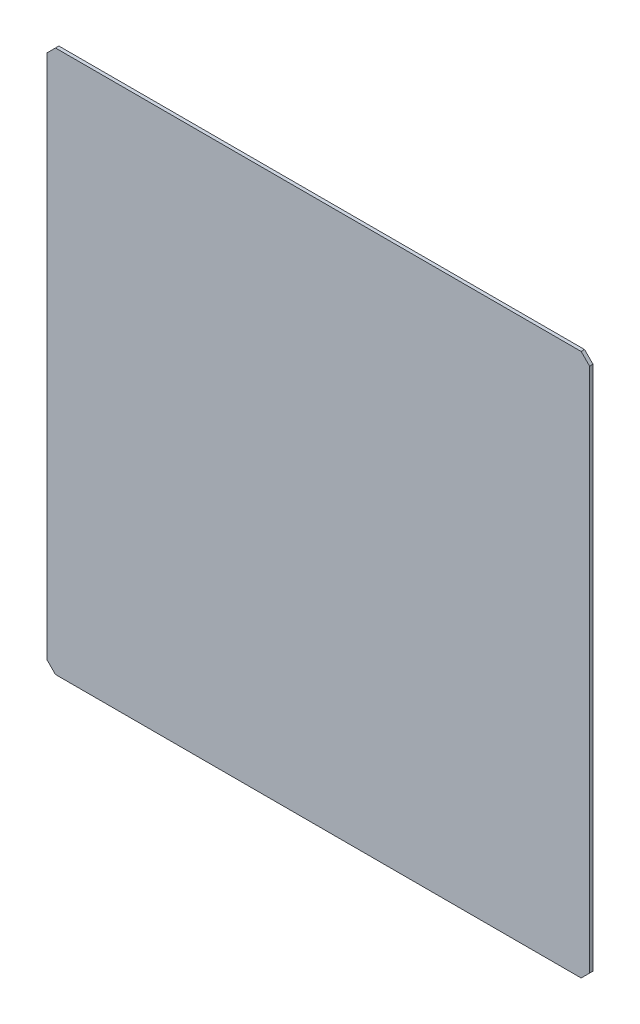
SolidWorks part; units mm, degrees
ref_plane "Front Plane" through (0, 0, 0) normal (0, 0, 1) x (1, 0, 0)
ref_plane "Top Plane" through (0, 0, 0) normal (0, 1, 0) x (1, 0, 0)
ref_plane "Right Plane" through (0, 0, 0) normal (1, 0, 0) x (0, 0, -1)
sketch "Sketch2" plane through (0, 0, 0) normal (0, 0, 1) x (1, 0, 0)
  line L1 (-160, -160) -> (160, -160)
  line L2 (-160, -160) -> (-160, 160)
  line L3 (-160, 160) -> (160, 160)
  line L4 (160, -160) -> (160, 160)
  line L5 (-160, -160) -> (160, 160) construction
  line L6 (-160, 160) -> (160, -160) construction
  point P0 (0, 0)
  dimension "D2" = 320
  dimension "D1" = 320
extrude "Boss-Extrude1" add sketch "Sketch2" along normal blind 2
chamfer "Chamfer1" distance 5 angle 45 4 edges at (-160, -160, 1) (-160, 160, 1) (160, 160, 1) (160, -160, 1)
equation "\"heater_pad_x\"= \"heater_pad_x@print_bed.Assembly\""
equation "\"heater_pad_y\"= \"heater_pad_y@print_bed.Assembly\""
equation "\"heater_pad_z\"= 2"
equation "\"D2@Sketch2\" = \"heater_pad_y\""
equation "\"D1@Sketch2\"= \"heater_pad_x\""
equation "\"D1@Boss-Extrude1\"=\"heater_pad_z\""
